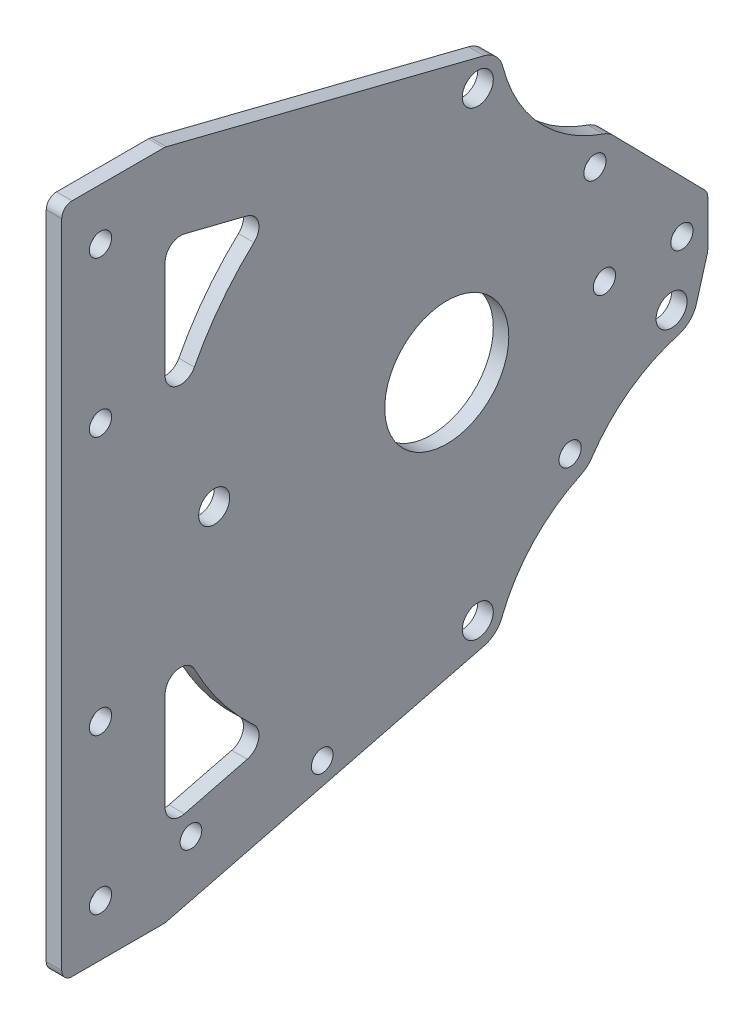
SolidWorks part; units mm, degrees
material "5052-H34"
ref_plane "正面" through (0, 0, 0) normal (0, 0, 1) x (1, 0, 0)
ref_plane "平面" through (0, 0, 0) normal (0, 1, 0) x (1, 0, 0)
ref_plane "右側面" through (0, 0, 0) normal (1, 0, 0) x (0, 0, -1)
sketch "ｽｹｯﾁ1" plane through (0, 0, 0) normal (1, 0, 0) x (0, 0, -1)
  line L0 (125, 65) -> (117.85, 65) construction
  line L1 (0, 0) -> (20, 0)
  line L2 (0, 0) -> (0, 130)
  line L3 (0, 130) -> (20, 130)
  line L5 (74.5, 65) -> (74.5, 53) construction
  line L6 (80.5, 65) -> (80.5, 20.4) construction
  line L7 (74.5, 53.7) -> (118, 53.7) construction
  line L8 (20, 130) -> (81.7216, 114.4485)
  line L9 (20, 0) -> (81.7216, 15.5515)
  line L10 (74.5, 65) -> (103.1703, 85.0752) construction
  line L11 (74.5, 65) -> (98.3699, 39.4026) construction
  line L12 (125, 70) -> (125, 60)
  line L13 (125, 60) -> (122.8076, 52.3264)
  line L14 (125, 70) -> (106.7361, 88.5802)
  line L15 (117.85, 65) -> (113.611, 65) construction
  line L16 (113.611, 65) -> (0, 65) construction
  line L17 (0, 12) -> (488.3237, 12) construction
  circle A0 centre (7.5, 120) radius 2.15
  circle A1 centre (7.5, 90) radius 2.15
  circle A2 centre (7.5, 40) radius 2.15
  circle A3 centre (7.5, 10) radius 2.15
  circle A4 centre (74.5, 65) radius 12
  circle A5 centre (29.5, 65) radius 3
  circle A6 centre (80.5, 20.4) radius 3
  circle A7 centre (118, 53.7) radius 3
  circle A8 centre (80.5, 109.6) radius 3
  arc A9 (85.3461, 110.831) -> (81.7216, 114.4485) centre (80.5, 109.6) ccw
  arc A10 (119.3587, 48.8881) -> (122.8076, 52.3264) centre (118, 53.7) ccw
  arc A11 (81.7216, 15.5515) -> (85.1565, 18.5787) centre (80.5, 20.4) ccw
  circle A12 centre (74.5, 65) radius 20 construction
  arc A15 (106.7361, 88.5802) -> (104.7778, 89.8097) centre (103.1703, 85.0752) ccw
  circle A16 centre (103.1703, 85.0752) radius 2.15
  arc A17 (85.3461, 110.831) -> (104.7778, 89.8097) centre (114.4226, 118.2171) ccw
  arc A18 (113.611, 65) -> (108.1554, 84.6897) centre (138.0661, 82.3766) cw construction
  arc A19 (100.4736, 34.8667) -> (102.5329, 36.6333) centre (98.3699, 39.4026) ccw
  circle A20 centre (98.3699, 39.4026) radius 2.15
  arc A22 (85.1565, 18.5787) -> (100.4736, 34.8667) centre (113.0955, 7.6511) cw
  arc A23 (119.3587, 48.8881) -> (102.5329, 36.6333) centre (127.511, 20.017) ccw
  circle A24 centre (105, 65) radius 2.15
  circle A25 centre (120, 65) radius 2.15
  arc A26 (122.8076, 52.3264) -> (120.8666, 57.7967) centre (118, 53.7) ccw construction
  arc A27 (120.8666, 57.7967) -> (113.611, 65) centre (138.0661, 82.3766) cw construction
  arc A28 (108.1554, 84.6897) -> (106.7361, 88.5802) centre (103.1703, 85.0752) ccw construction
  circle A29 centre (25, 12) radius 2.1
  circle A30 centre (50.4, 12) radius 2.1
  dimension "D3" = 30
  dimension "D4" = 4.3
  dimension "D5" = 7.5
  dimension "D6" = 10
  dimension "D7" = 6
  dimension "D8" = 45
  dimension "D10" = 24
  dimension "D11" = 74.5
  dimension "D12" = 44.6
  dimension "D14" = 43.5
  dimension "D15" = 44.6
  dimension "D16" = 10
  dimension "D17" = 40
  dimension "D18" = 30
  dimension "D20" = 10
  dimension "D23" = 47
  dimension "D24" = 4.3
  dimension "D26" = 30
  dimension "D27" = 15
  dimension "D28" = 105
  dimension "D30" = 25.4
  dimension "D31" = 4.2
  dimension "D32" = 25
  dimension "D1" = 130
  dimension "D9" = 6
  dimension "D13" = 11.3
  dimension "D19" = 20
  dimension "D21" = 20
  dimension "D22" = 35
  dimension "D25" = 35
  dimension "D29" = 5
  dimension "D33" = 12
extrude "ﾎﾞｽ - 押し出し1" add sketch "ｽｹｯﾁ1" along normal blind 3
sketch "ｽｹｯﾁ2" plane through (3, 0, 0) normal (1, 0, 0) x (0, 0, -1)
  line L0 (20, 114.5312) -> (20, 72.3993)
  line L1 (20, 114.5312) -> (41.614, 109.0853)
  line L2 (81.7216, 114.4485) -> (20, 130) construction
  line L3 (20, 15.4688) -> (41.614, 20.9147)
  line L4 (20, 0) -> (81.7216, 15.5515) construction
  line L7 (20, 57.6007) -> (20, 15.4688)
  line L9 (0, 130) -> (0, 0) construction
  arc A0 (20, 57.6007) -> (41.614, 20.9147) centre (74.5, 65) ccw
  arc A3 (41.614, 109.0853) -> (20, 72.3993) centre (74.5, 65) ccw
  dimension "D3" = 110
  dimension "D1" = 15
  dimension "D2" = 15
  dimension "D4" = 20
extrude "ｶｯﾄ - 押し出し1" cut sketch "ｽｹｯﾁ2" against normal up to surface (3 mm away) up to face at (0, 62.54, -79.7999)
fillet "ﾌｨﾚｯﾄ1" radius 2 4 edges at (1.5, 0, -20) (1.5, 0, 0) (1.5, 130, -20) (1.5, 130, 0)
fillet "ﾌｨﾚｯﾄ2" radius 2 2 edges at (1.5, 60, -125) (1.5, 70, -125)
fillet "ﾌｨﾚｯﾄ3" radius 3 6 edges at (1.5, 15.4688, -20) (1.5, 20.9147, -41.614) (1.5, 57.6007, -20) (1.5, 72.3993, -20) (1.5, 109.0853, -41.614) (1.5, 114.5312, -20)
